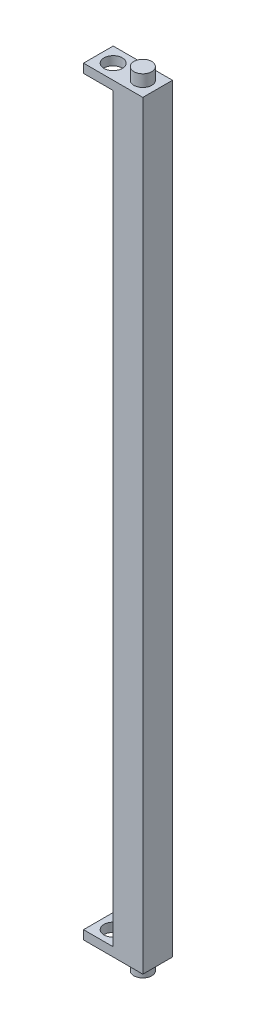
SolidWorks part; units mm, degrees
ref_plane "前视基准面" through (0, 0, 0) normal (0, 0, 1) x (1, 0, 0)
ref_plane "上视基准面" through (0, 0, 0) normal (0, 1, 0) x (1, 0, 0)
ref_plane "右视基准面" through (0, 0, 0) normal (1, 0, 0) x (0, 0, -1)
other "Configuration Table"
sketch "草图2" plane through (0, 0, 0) normal (0, 1, 0) x (1, 0, 0)
  line L1 (5, -2.5) -> (-5, -2.5)
  line L2 (5, -2.5) -> (5, 2.5)
  line L3 (5, 2.5) -> (-5, 2.5)
  line L4 (-5, -2.5) -> (-5, 2.5)
  line L5 (5, -2.5) -> (-5, 2.5) construction
  line L6 (5, 2.5) -> (-5, -2.5) construction
  circle A0 centre (2.5, 0) radius 1.55
  circle A1 centre (-2.5, 0) radius 1.55
  point P0 (0, 0)
  dimension "D3" = 3.1
  dimension "D4" = 3.1
  dimension "D1" = 10
  dimension "D2" = 2.5
  dimension "D5" = 2.5
  dimension "D6" = 5
extrude "凸台-拉伸1" add sketch "草图2" along normal blind 1.5 contours L3 L4 L1 L2
sketch "草图3" plane through (0, 0, 0) normal (0, -1, 0) x (1, 0, 0)
  line L0 (5, -2.5) -> (-5, -2.5) construction
  circle A0 centre (-2.5, 0) radius 1.55
  dimension "D3" = 3.1
  dimension "D1" = 2.5
  dimension "D2" = 2.5
extrude "切除-拉伸1" cut sketch "草图3" against normal blind 1.5
sketch "草图4" plane through (0, 0, 0) normal (0, -1, 0) x (1, 0, 0)
  line L0 (0, 2.5) -> (0, -2.5)
  line L1 (5, 2.5) -> (-5, 2.5) construction
  line L2 (5, -2.5) -> (-5, -2.5) construction
  line L3 (0, -2.5) -> (5, -2.5)
  line L4 (5, -2.5) -> (5, 2.5)
  line L5 (5, 2.5) -> (0, 2.5)
  dimension "D1" = 5
extrude "凸台-拉伸2" add sketch "草图4" along normal blind 125
sketch "草图5" plane through (0, -125, 0) normal (0, -1, 0) x (1, 0, 0)
  line L1 (5, 2.5) -> (-5, 2.5)
  line L2 (5, 2.5) -> (5, -2.5)
  line L3 (5, -2.5) -> (-5, -2.5)
  line L4 (-5, 2.5) -> (-5, -2.5)
extrude "凸台-拉伸3" add sketch "草图5" along normal blind 1.5
sketch "草图6" plane through (0, -126.5, 0) normal (0, -1, 0) x (1, 0, 0)
  line L0 (-5, 2.5) -> (-5, -2.5) construction
  circle A0 centre (-2.5, 0) radius 1.55
  dimension "D2" = 3.1
  dimension "D1" = 2.5
extrude "切除-拉伸2" cut sketch "草图6" against normal blind 1.5
sketch "草图7" plane through (0, 1.5, 0) normal (0, 1, 0) x (1, 0, 0)
  line L0 (5, -2.5) -> (5, 2.5) construction
  line L1 (5, -2.5) -> (-5, -2.5) construction
  circle A0 centre (2.5, 0) radius 1.5
  dimension "D1" = 3
  dimension "D2" = 2.5
  dimension "D3" = 2.5
extrude "凸台-拉伸4" add sketch "草图7" along normal blind 2 contours A0
sketch "草图8" plane through (0, -126.5, 0) normal (0, -1, 0) x (1, 0, 0)
  line L0 (-5, -2.5) -> (5, -2.5) construction
  line L1 (5, -2.5) -> (5, 2.5) construction
  circle A0 centre (2.5, 0) radius 1.5
  dimension "D3" = 3
  dimension "D1" = 2.5
  dimension "D2" = 2.5
extrude "凸台-拉伸5" add sketch "草图8" along normal blind 2
